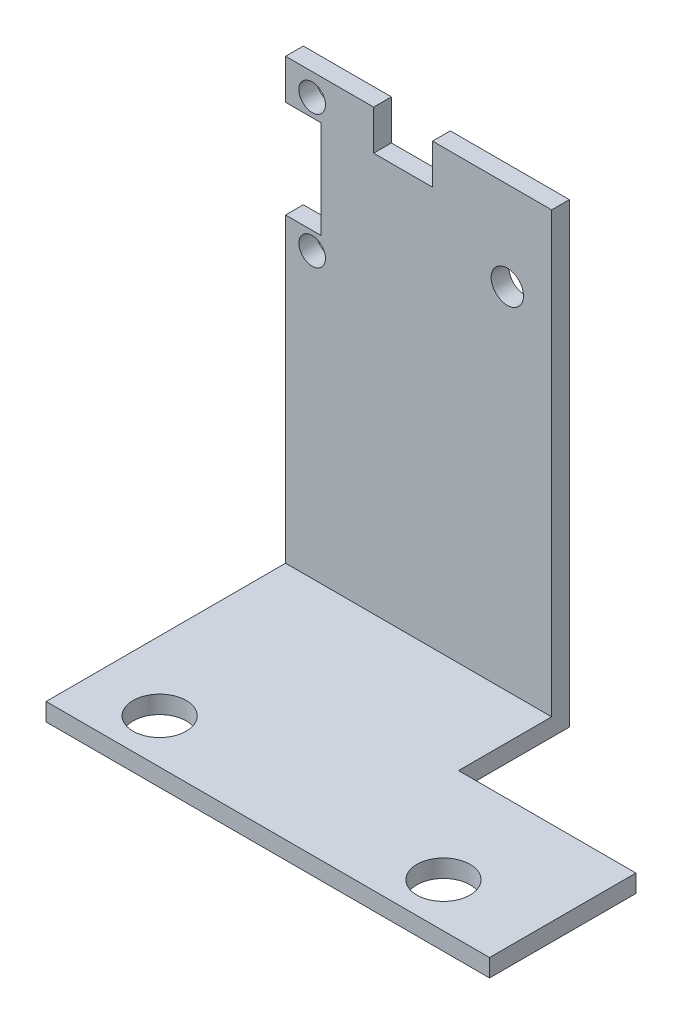
SolidWorks part; units mm, degrees
ref_plane "Ebene vorne" through (0, 0, 0) normal (0, 0, 1) x (1, 0, 0)
ref_plane "Ebene oben" through (0, 0, 0) normal (0, 1, 0) x (1, 0, 0)
ref_plane "Ebene rechts" through (0, 0, 0) normal (1, 0, 0) x (0, 0, -1)
sketch "Skizze1" plane through (0, 0, 0) normal (0, 1, 0) x (1, 0, 0)
  line L1 (-25, -14.5) -> (25, -14.5)
  line L2 (-25, -14.5) -> (-25, 14.5)
  line L3 (-25, 14.5) -> (25, 14.5)
  line L4 (25, -14.5) -> (25, 14.5)
  line L5 (-25, -14.5) -> (25, 14.5) construction
  line L6 (-25, 14.5) -> (25, -14.5) construction
  circle A0 centre (14.8024, -9.5) radius 3
  circle A1 centre (-17.1976, -9.5) radius 3
  point P0 (0, 0)
  dimension "D2" = 6
  dimension "D3" = 6
  dimension "D1" = 32
  dimension "D4" = 50
  dimension "D5" = 5
  dimension "D6" = 24
  dimension "D7" = 5
extrude "Aufsatz-Linear austragen1" add sketch "Skizze1" along normal blind 2
sketch "Skizze2" plane through (0, 2, 0) normal (0, 1, 0) x (1, 0, 0)
  line L1 (-25, 14.5) -> (5, 14.5)
  line L2 (-25, 14.5) -> (-25, 12.5)
  line L3 (-25, 12.5) -> (5, 12.5)
  line L4 (5, 14.5) -> (5, 12.5)
  dimension "D1" = 2
  dimension "D2" = 5
extrude "Aufsatz-Linear austragen2" add sketch "Skizze2" along normal blind 49.5
sketch "Skizze3" plane through (0, 0, -12.5) normal (0, 0, 1) x (1, 0, 0)
  line L0 (-25, 51.5) -> (5, 51.5) construction
  line L1 (-25, 51.5) -> (-25, 2) construction
  line L2 (-25, 47) -> (-21, 47)
  line L3 (-25, 47) -> (-25, 36)
  line L4 (-25, 36) -> (-21, 36)
  line L5 (-21, 47) -> (-21, 36)
  line L7 (-15.0686, 51.5) -> (-8.4293, 51.5)
  line L8 (-15.0686, 51.5) -> (-15.0686, 47)
  line L9 (-15.0686, 47) -> (-8.4293, 47)
  line L10 (-8.4293, 51.5) -> (-8.4293, 47)
  circle A0 centre (-22, 49) radius 1.5
  circle A1 centre (-22, 34) radius 1.5
  circle A2 centre (0, 41.5) radius 1.8226
  dimension "D3" = 3
  dimension "D4" = 3
  dimension "D1" = 0
  dimension "D2" = 10
  dimension "D5" = 15
  dimension "D6" = 2.5
  dimension "D7" = 22
  dimension "D8" = 2
  dimension "D9" = 2
  dimension "D10" = 4
extrude "Schnitt-Linear austragen1" cut sketch "Skizze3" against normal blind 49.5
sketch "Skizze4" plane through (0, 2, 0) normal (0, 1, 0) x (1, 0, 0)
  line L1 (25, 14.5) -> (5, 14.5)
  line L2 (25, 14.5) -> (25, 2)
  line L3 (25, 2) -> (5, 2)
  line L4 (5, 14.5) -> (5, 2)
  dimension "D1" = 20
  dimension "D2" = 12.5
extrude "Schnitt-Linear austragen2" cut sketch "Skizze4" against normal blind 49.5
